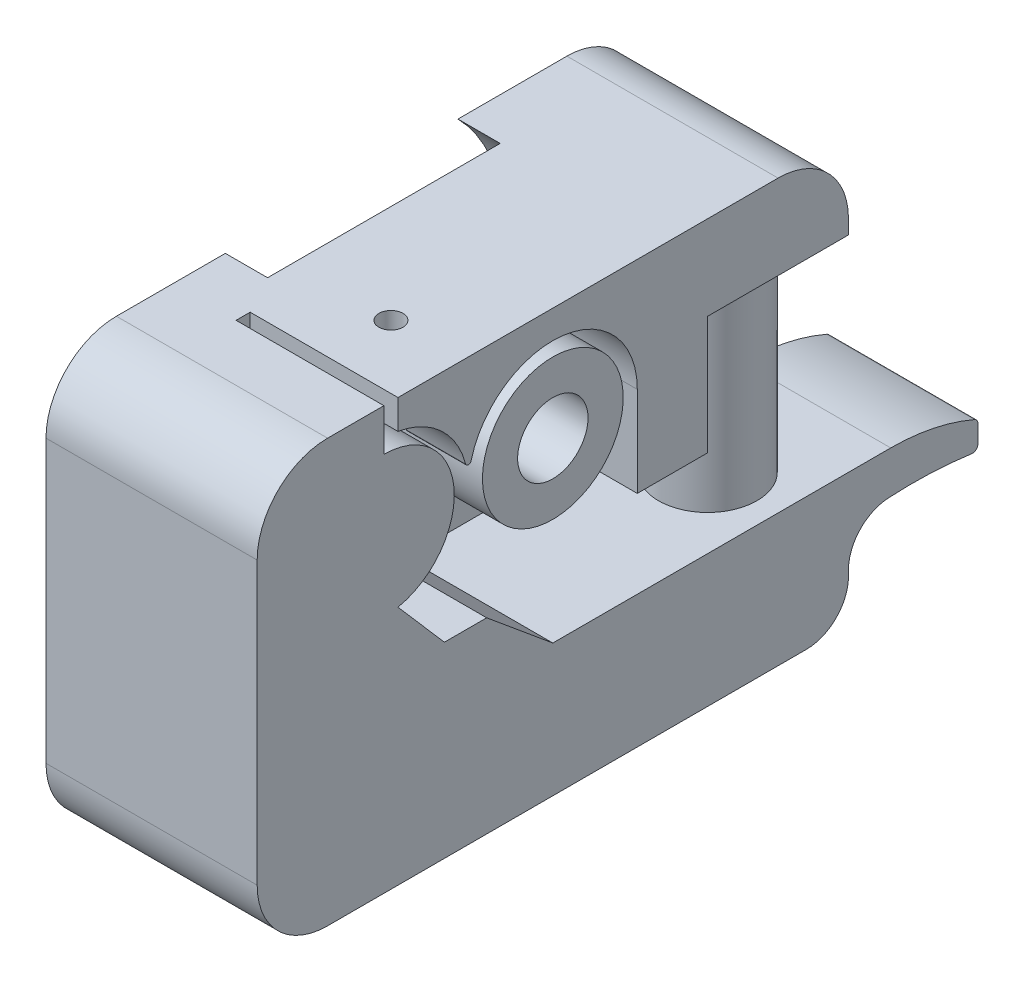
SolidWorks part; units mm, degrees
ref_plane "Front Plane" through (0, 0, 0) normal (0, 0, 1) x (1, 0, 0)
ref_plane "Top Plane" through (0, 0, 0) normal (0, 1, 0) x (1, 0, 0)
ref_plane "Right Plane" through (0, 0, 0) normal (1, 0, 0) x (0, 0, -1)
sketch "Sketch1" plane through (0, 0, 0) normal (1, 0, 0) x (0, 0, -1)
  line L1 (21, -15) -> (-21, -15)
  line L2 (21, -15) -> (21, 15)
  line L3 (21, 15) -> (-21, 15)
  line L4 (-21, -15) -> (-21, 15)
  line L5 (21, -15) -> (-21, 15) construction
  line L6 (21, 15) -> (-21, -15) construction
  point P0 (0, 0)
  dimension "D1" = 30
  dimension "D2" = 42
extrude "Boss-Extrude1" add sketch "Sketch1" along normal blind 15
fillet "Fillet1" radius 5 3 edges at (7.5, -15, 21) (7.5, 15, -21) (7.5, 15, 21)
sketch "Sketch2" plane through (15, 0, 0) normal (1, 0, 0) x (0, 0, -1)
  line L0 (16, 15) -> (-16, 15) construction
  line L1 (21, 9) -> (11, 9)
  line L2 (21, 9) -> (21, -5.6)
  line L3 (21, -5.6) -> (11, -5.6)
  line L4 (11, 9) -> (11, 0.6)
  line L5 (21, -15) -> (21, 10) construction
  line L6 (-16, -15) -> (21, -15) construction
  line L7 (0, -5.6) -> (-4.7, -1.7)
  line L8 (11, -5.6) -> (0, -5.6)
  line L10 (11, 0.6) -> (6, 0.6)
  line L12 (-4.7, -1.7) -> (-7.7, -1.7)
  line L13 (-21, 10) -> (-21, -10) construction
  line L14 (-11, 2.101) -> (-7.7, -1.7)
  line L15 (6, 7) -> (6, 0.6)
  line L16 (-11, 12.9161) -> (-11, 15)
  line L17 (-11, 15) -> (-12, 15)
  line L18 (-12, 15) -> (-12, 12)
  circle A0 centre (-12, 7) radius 2 construction
  arc A1 (-11, 12.9161) -> (-6, 7) centre (-12, 7) cw
  arc A2 (6, 7) -> (-6, 7) centre (0, 7) ccw
  arc A3 (-12, 12) -> (-11, 2.101) centre (-12, 7) cw
  dimension "D7" = 6
  dimension "D9" = 12
  dimension "D10" = 4
  dimension "D14" = 1
  dimension "D1" = 6
  dimension "D2" = 10
  dimension "D3" = 9.4
  dimension "D4" = 6.2
  dimension "D5" = 8
  dimension "D6" = 9
  dimension "D8" = 13.3
  dimension "D11" = 1.3
  dimension "D12" = 3
  dimension "D13" = 1
extrude "Cut-Extrude1" cut sketch "Sketch2" against normal blind 10.5
fillet "Fillet2" radius 0.2 1 edges at (9.75, 7, 6)
sketch "Sketch3" plane through (0, -5.6, 0) normal (0, 1, 0) x (1, 0, 0)
  line L0 (4.5, 21) -> (15, 21) construction
  line L1 (15, 0) -> (15, 21) construction
  circle A0 centre (10, 16) radius 3.5
  dimension "D1" = 5
  dimension "D2" = 5
  dimension "D3" = 7
extrude "Boss-Extrude2" add sketch "Sketch3" along normal up to surface (14.6 mm away) up to face at (9.75, 9, -16)
sketch "Sketch4" plane through (4.5, 0, 0) normal (1, 0, 0) x (0, 0, -1)
  circle A0 centre (0, 7) radius 5
  arc A1 (6, 7) -> (-5.8065, 8.5117) centre (0, 7) ccw construction
  dimension "D1" = 1
extrude "Boss-Extrude3" add sketch "Sketch4" along normal blind 10.5
sketch "Sketch5" plane through (0, -15, 0) normal (0, -1, 0) x (1, 0, 0)
  line L0 (0, 21) -> (15, 21) construction
  line L1 (15, 16) -> (15, -21) construction
  circle A0 centre (10, 6.5) radius 3
  dimension "D1" = 14.5
  dimension "D2" = 5
  dimension "D3" = 6
extrude "Cut-Extrude2" cut sketch "Sketch5" against normal blind 2 draft 47
sketch "Sketch6" plane through (0, -13, 0) normal (0, -1, 0) x (1, 0, 0)
  circle A0 centre (10, 6.5) radius 0.8553 construction
  circle A1 centre (10, 6.5) radius 0.8553
extrude "Cut-Extrude3" cut sketch "Sketch6" against normal through all
sketch "Sketch7" plane through (15, 0, 0) normal (1, 0, 0) x (0, 0, -1)
  circle A0 centre (0, 7) radius 2.5
  circle A1 centre (0, 7) radius 5 construction
  dimension "D1" = 5
extrude "Cut-Extrude4" cut sketch "Sketch7" against normal through all
sketch "Sketch8" plane through (15, 0, 0) normal (1, 0, 0) x (0, 0, -1)
  line L0 (21, -5.6) -> (24, -5.6)
  line L1 (30.2, -6.9413) -> (30.2, -8.9)
  line L2 (21, -5.6) -> (21, -8.9)
  line L3 (21, -15) -> (21, -5.6) construction
  arc A0 (24, -5.6) -> (30.2, -6.9413) centre (24, -20.6) cw
  arc A1 (21, -8.9) -> (30.2, -8.9) centre (25.6, -38.5452) cw
  dimension "D2" = 15
  dimension "D5" = 30
  dimension "D1" = 9.2
  dimension "D3" = 3
  dimension "D4" = 3.3
extrude "Boss-Extrude4" add sketch "Sketch8" against normal blind 10.5
fillet "Fillet3" radius 3 2 edges at (7.5, -15, -21) (9.75, -8.9, -21)
fillet "Fillet4" radius 0.4 2 edges at (9.75, -6.9413, -30.2) (9.75, -8.9, -30.2)
sketch "Sketch9" plane through (0, 0, 0) normal (-1, 0, 0) x (0, 0, 1)
  circle A0 centre (0, 7) radius 11.5
  dimension "D1" = 23
extrude "Cut-Extrude5" cut sketch "Sketch9" against normal blind 3
